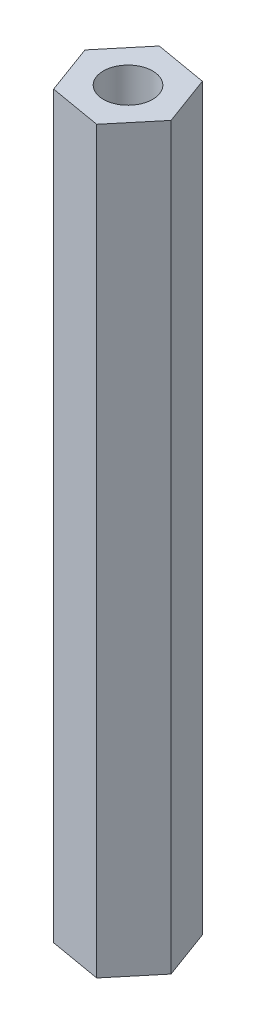
SolidWorks part; units mm, degrees
ref_plane "Front Plane" through (0, 0, 0) normal (0, 0, 1) x (1, 0, 0)
ref_plane "Top Plane" through (0, 0, 0) normal (0, 1, 0) x (1, 0, 0)
ref_plane "Right Plane" through (0, 0, 0) normal (1, 0, 0) x (0, 0, -1)
sketch "Sketch1" plane through (0, 0, 0) normal (0, 1, 0) x (1, 0, 0)
  line L0 (1.1114, -3.016) -> (3.1677, -0.5455)
  line L1 (3.1677, -0.5455) -> (2.0562, 2.4705)
  line L2 (2.0562, 2.4705) -> (-1.1114, 3.016)
  line L3 (-1.1114, 3.016) -> (-3.1677, 0.5455)
  line L4 (-3.1677, 0.5455) -> (-2.0562, -2.4705)
  line L5 (-2.0562, -2.4705) -> (1.1114, -3.016)
  circle A0 centre (0, 0) radius 1.5
  dimension "D1" = 3
  dimension "D2" = 5.5673
  dimension "D3" = 240
  dimension "D4" = 240
  dimension "D5" = 240
extrude "Boss-Extrude1" add sketch "Sketch1" along normal blind 45
